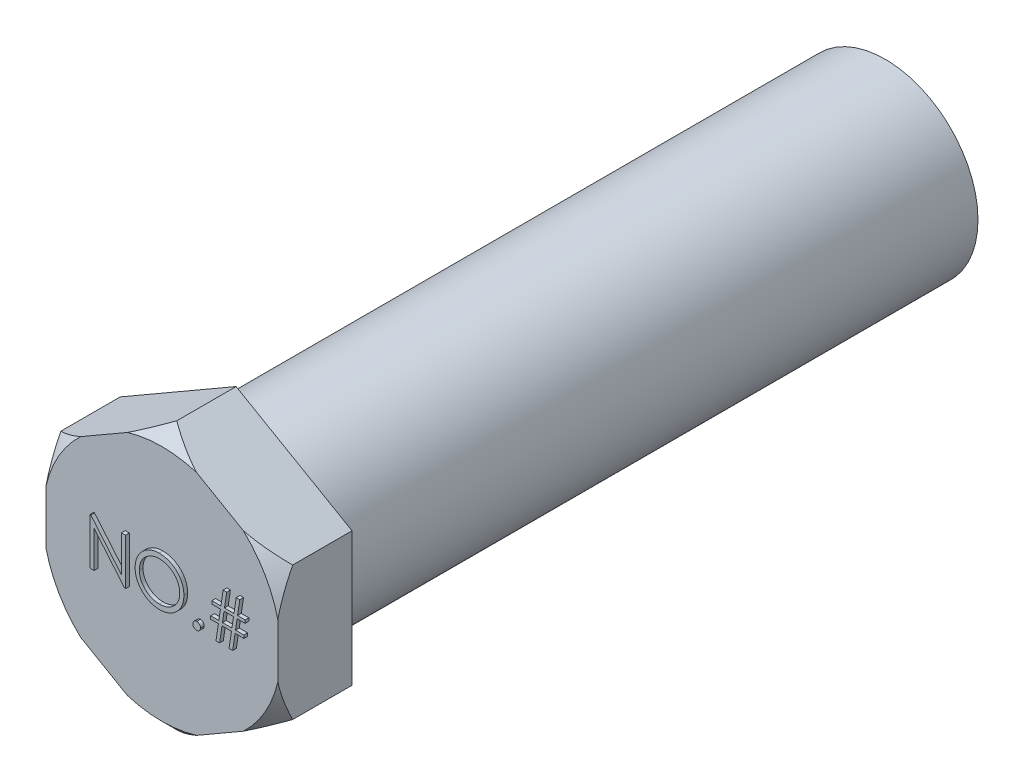
SolidWorks part; units mm, degrees
ref_plane "Front Plane" through (0, 0, 0) normal (0, 0, 1) x (1, 0, 0)
ref_plane "Top Plane" through (0, 0, 0) normal (0, 1, 0) x (1, 0, 0)
ref_plane "Right Plane" through (0, 0, 0) normal (1, 0, 0) x (0, 0, -1)
sketch "Sketch1" plane through (0, 0, 0) normal (0, 0, 1) x (1, 0, 0)
  circle A0 centre (0, 0) radius 5
  dimension "D1" = 10
extrude "Boss-Extrude1" add sketch "Sketch1" against normal blind 35
cosmetic thread "Cosmetic Thread1" parameters "D1"=22, "D2"=8
sketch "Sketch2" plane through (0, 0, 0) normal (0, 0, 1) x (1, 0, 0)
  line L1 (-6.25, -3.6084) -> (0, -7.2169)
  line L2 (0, -7.2169) -> (6.25, -3.6084)
  line L3 (6.25, -3.6084) -> (6.25, 3.6084)
  line L4 (6.25, 3.6084) -> (0, 7.2169)
  line L5 (0, 7.2169) -> (-6.25, 3.6084)
  line L6 (-6.25, 3.6084) -> (-6.25, -3.6084)
  circle A0 centre (0, 0) radius 6.25 construction
  dimension "D1" = 12.5
extrude "Boss-Extrude2" add sketch "Sketch2" along normal blind 4
sketch "Sketch3" plane through (0, 0, 0) normal (1, 0, 0) x (0, 0, -1)
  line L0 (-3.2, 7.2169) -> (-4, 7.2169)
  line L1 (-4, 7.2169) -> (0, 7.2169) construction
  line L2 (-4, 7.2169) -> (-4, 6.4169)
  line L3 (-4, 3.6084) -> (-4, 7.2169) construction
  line L4 (-4, 6.4169) -> (-3.2, 7.2169)
  line L5 (0, 0) -> (-8.6472, 0) construction
  dimension "D1" = 0.8
revolve "Cut-Revolve1" cut sketch "Sketch3" angle 360 about L5
sketch "Sketch4" plane through (0, 0, 4) normal (0, 0, 1) x (1, 0, 0)
  text T0 "NO.#" font "Century Gothic" height 2.5
  point P2 (0, 0)
  dimension "D1" = 1
  dimension "D2" = 4
extrude "Boss-Extrude3" add sketch "Sketch4" along normal blind 0.2
